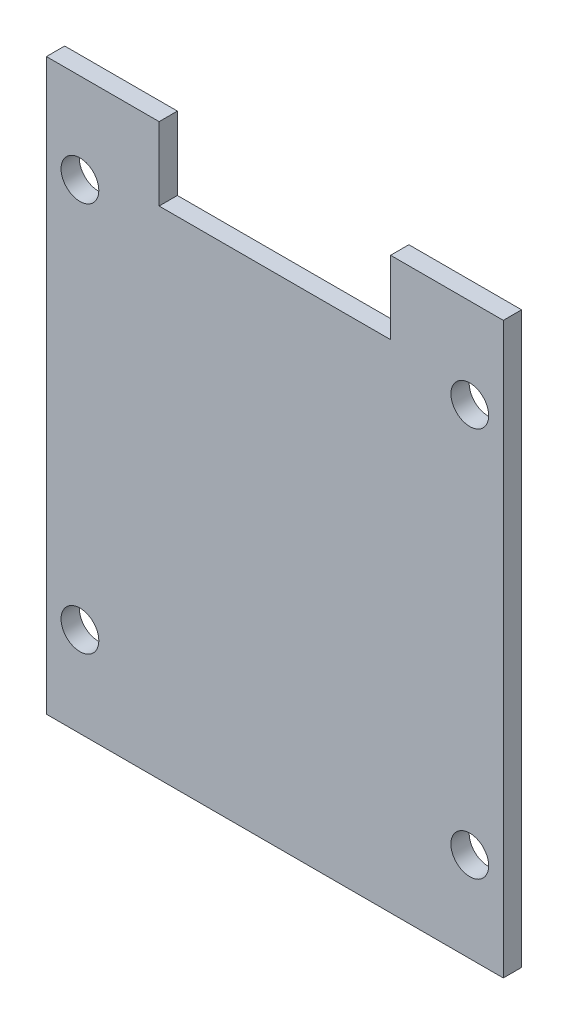
SolidWorks part; units mm, degrees
ref_plane "Front Plane" through (0, 0, 0) normal (0, 0, 1) x (1, 0, 0)
ref_plane "Top Plane" through (0, 0, 0) normal (0, 1, 0) x (1, 0, 0)
ref_plane "Right Plane" through (0, 0, 0) normal (1, 0, 0) x (0, 0, -1)
sketch "Sketch1" plane through (0, 0, 0) normal (0, 0, 1) x (1, 0, 0)
  line L1 (-37.5, 46.75) -> (37.5, 46.75)
  line L2 (-37.5, 46.75) -> (-37.5, -46.75)
  line L3 (-37.5, -46.75) -> (37.5, -46.75)
  line L4 (37.5, 46.75) -> (37.5, -46.75)
  line L5 (-37.5, 46.75) -> (37.5, -46.75) construction
  line L6 (-37.5, -46.75) -> (37.5, 46.75) construction
  point P0 (0, 0)
  dimension "D1" = 75
  dimension "D2" = 93.5
extrude "Boss-Extrude1" add sketch "Sketch1" along normal blind 3
sketch "Sketch2" plane through (0, 0, 3) normal (0, 0, 1) x (1, 0, 0)
  line L0 (37.5, 46.75) -> (-37.5, 46.75) construction
  line L1 (-37.5, 46.75) -> (-37.5, -46.75) construction
  circle A0 centre (-32, 32) radius 3.1
  dimension "D3" = 6.2
  dimension "D1" = 14.75
  dimension "D2" = 5.5
extrude "Cut-Extrude1" cut sketch "Sketch2" against normal through all
pattern_linear "LPattern1" count 2 spacing 64 along (1, 0, 0) count 2 spacing 64 along (0, -1, 0) of "Cut-Extrude1"
sketch "Sketch3" plane through (0, 0, 3) normal (0, 0, 1) x (1, 0, 0)
  line L0 (37.5, 46.75) -> (-37.5, 46.75) construction
  line L1 (19, 46.75) -> (-19, 46.75)
  line L2 (19, 46.75) -> (19, 34.75)
  line L3 (19, 34.75) -> (-19, 34.75)
  line L4 (-19, 46.75) -> (-19, 34.75)
  line L5 (0, 46.75) -> (0, 24.2736) construction
  dimension "D1" = 12
  dimension "D2" = 38
extrude "Cut-Extrude2" cut sketch "Sketch3" against normal through all contours L3 L4 L1 L2
